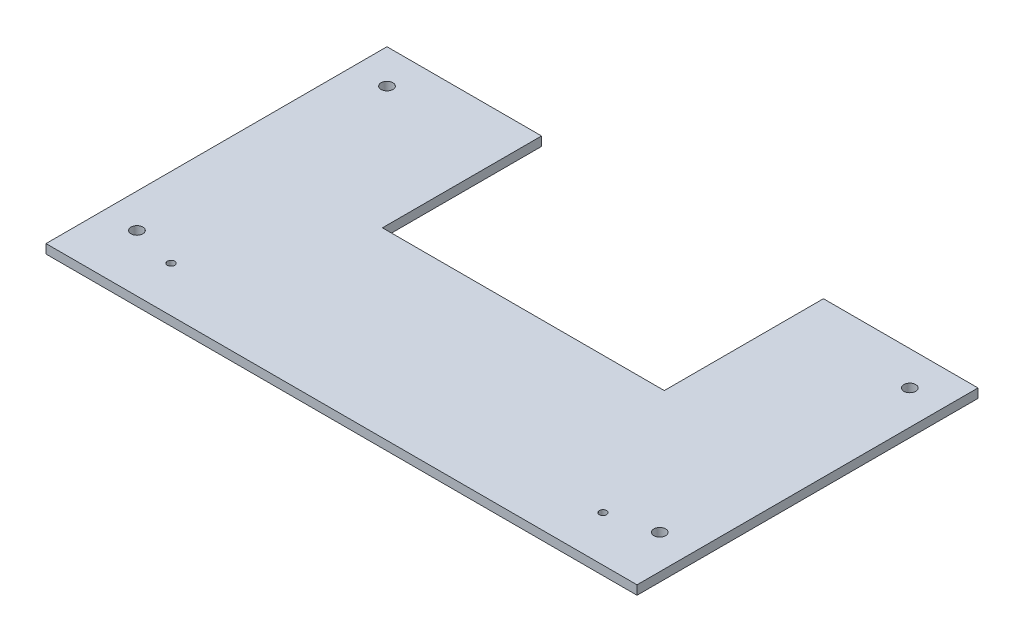
SolidWorks part; units mm, degrees
ref_plane "Alzado" through (0, 0, 0) normal (0, 0, 1) x (1, 0, 0)
ref_plane "Planta" through (0, 0, 0) normal (0, 1, 0) x (1, 0, 0)
ref_plane "Vista lateral" through (0, 0, 0) normal (1, 0, 0) x (0, 0, -1)
sketch "Croquis1" plane through (0, 0, 0) normal (0, 1, 0) x (1, 0, 0)
  line L1 (-130, -75) -> (130, -75)
  line L2 (-130, -75) -> (-130, 75)
  line L3 (-130, 75) -> (130, 75)
  line L4 (130, -75) -> (130, 75)
  line L5 (-130, -75) -> (130, 75) construction
  line L6 (-130, 75) -> (130, -75) construction
  point P0 (0, 0)
  dimension "D1" = 260
  dimension "D2" = 150
extrude "Saliente-Extruir1" add sketch "Croquis1" along normal blind 4
sketch "Croquis2" plane through (0, 4, 0) normal (0, 1, 0) x (1, 0, 0)
  line L0 (130, 75) -> (-130, 75) construction
  line L1 (-62, 5) -> (62, 5)
  line L2 (-62, 5) -> (-62, 75)
  line L3 (-62, 75) -> (62, 75)
  line L4 (62, 5) -> (62, 75)
  line L5 (130, -75) -> (130, 75) construction
  line L6 (-130, -75) -> (130, -75) construction
  circle A0 centre (95, -55) radius 1.6
  circle A1 centre (-95, -55) radius 1.6
  dimension "D4" = 3.2
  dimension "D1" = 62
  dimension "D2" = 62
  dimension "D3" = 70
  dimension "D5" = 35
  dimension "D6" = 20
  dimension "D7" = 2
extrude "Cortar-Extruir1" cut sketch "Croquis2" against normal blind 4
sketch "Croquis3" plane through (0, 4, 0) normal (0, 1, 0) x (1, 0, 0)
  line L0 (-62, 75) -> (-130, 75) construction
  line L1 (-130, 75) -> (-130, -75) construction
  circle A0 centre (-115, 60) radius 2.6
  circle A1 centre (115, 60) radius 2.6
  circle A2 centre (115, -50) radius 2.6
  circle A3 centre (-115, -50) radius 2.6
  dimension "D1" = 5.2
  dimension "D2" = 15
  dimension "D3" = 15
  dimension "D4" = 2
  dimension "D5" = 2
extrude "Cortar-Extruir2" cut sketch "Croquis3" against normal blind 4
